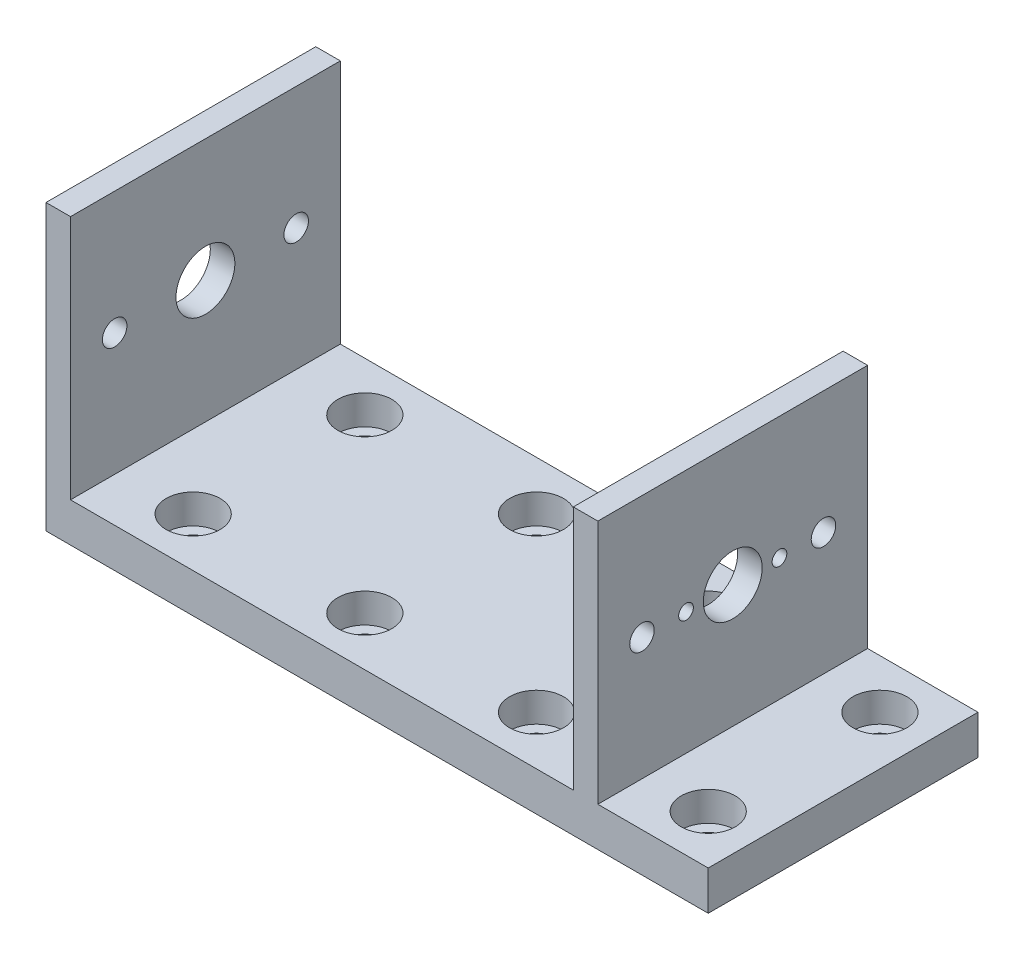
SolidWorks part; units mm, degrees
ref_plane "Front Plane" through (0, 0, 0) normal (0, 0, 1) x (1, 0, 0)
ref_plane "Top Plane" through (0, 0, 0) normal (0, 1, 0) x (1, 0, 0)
ref_plane "Right Plane" through (0, 0, 0) normal (1, 0, 0) x (0, 0, -1)
sketch "Sketch1" plane through (0, 0, 0) normal (0, 1, 0) x (1, 0, 0)
  line L0 (0, 14.013) -> (0, -13.1268) construction
  line L1 (-3.8771, 0) -> (4.5418, 0) construction
  line L2 (-35, 17.5) -> (-35, -17.5) construction
  line L3 (62.5, 27.5) -> (-62.5, 27.5)
  line L4 (-62.5, 27.5) -> (-62.5, -27.5)
  line L5 (62.5, -27.5) -> (-62.5, -27.5)
  line L6 (62.5, 27.5) -> (62.5, -27.5)
  circle A0 centre (-35, 0) radius 10 construction
  circle A1 centre (-52.5, 17.5) radius 3.25
  circle A2 centre (-52.5, -17.5) radius 3.25
  circle A3 centre (-17.5, -17.5) radius 3.25
  circle A4 centre (-17.5, 17.5) radius 3.25
  circle A5 centre (52.5, -17.5) radius 3.25
  circle A6 centre (17.5, -17.5) radius 3.25
  circle A7 centre (17.5, 17.5) radius 3.25
  circle A8 centre (35, 0) radius 10 construction
  circle A9 centre (52.5, 17.5) radius 3.25
  circle A10 centre (-52.5, 17.5) radius 5.5 construction
  circle A11 centre (-17.5, 17.5) radius 5.5 construction
  circle A12 centre (-17.5, -17.5) radius 5.5 construction
  circle A13 centre (-52.5, -17.5) radius 5.5 construction
  circle A14 centre (17.5, -17.5) radius 5.5 construction
  circle A15 centre (17.5, 17.5) radius 5.5 construction
  circle A16 centre (52.5, 17.5) radius 5.5 construction
  circle A17 centre (52.5, -17.5) radius 5.5 construction
  point P19 (-62.5, 0)
  point P33 (0, -27.5)
  point P34 (0, 27.5)
  dimension "D1" = 20
  dimension "D2" = 6.5
  dimension "D10" = 11
  dimension "D3" = 35
  dimension "D4" = 35
  dimension "D5" = 70
  dimension "D6" = 10
  dimension "D7" = 10
  dimension "D8" = 55
  dimension "D9" = 125
extrude "Boss-Extrude1" add sketch "Sketch1" along normal blind 8
sketch "Sketch5" plane through (0, 8, 0) normal (0, 1, 0) x (1, 0, 0)
  circle A0 centre (-52.5, 17.5) radius 5.5
  circle A1 centre (-17.5, 17.5) radius 5.5
  circle A2 centre (17.5, 17.5) radius 5.5
  circle A3 centre (52.5, 17.5) radius 5.5
  circle A4 centre (52.5, -17.5) radius 5.5
  circle A5 centre (17.5, -17.5) radius 5.5
  circle A6 centre (-17.5, -17.5) radius 5.5
  circle A7 centre (-52.5, -17.5) radius 5.5
  dimension "D1" = 11
extrude "Cut-Extrude1" cut sketch "Sketch5" against normal blind 6
sketch "Sketch3" plane through (-62.5, 0, 0) normal (-1, 0, 0) x (0, 0, 1)
  line L0 (-27.5, 0) -> (-27.5, 8)
  line L1 (-27.5, 8) -> (27.5, 8) construction
  line L2 (-27.5, 8) -> (27.5, 8)
  line L3 (27.5, 8) -> (27.5, 0)
  line L4 (27.5, 0) -> (-27.5, 0)
extrude "Boss-Extrude3" add sketch "Sketch3" along normal blind 10
sketch "Sketch4" plane through (0, 8, 0) normal (0, 1, 0) x (1, 0, 0)
  line L0 (-72.5, 27.5) -> (-72.5, -27.5)
  line L1 (-72.5, -27.5) -> (-67.5, -27.5)
  line L2 (-72.5, -27.5) -> (62.5, -27.5) construction
  line L3 (-67.5, -27.5) -> (-67.5, 27.5)
  line L4 (62.5, 27.5) -> (-72.5, 27.5) construction
  line L5 (-67.5, 27.5) -> (-72.5, 27.5)
  line L6 (37.5, 27.5) -> (37.5, -27.5) construction
  line L11 (62.5, -27.5) -> (62.5, 27.5) construction
  line L12 (40, 27.5) -> (35, 27.5)
  line L13 (35, 27.5) -> (35, -27.5)
  line L14 (35, -27.5) -> (40, -27.5)
  line L15 (40, 27.5) -> (40, -27.5)
  dimension "D1" = 5
  dimension "D2" = 25
  dimension "D3" = 5
extrude "Boss-Extrude4" add sketch "Sketch4" along normal blind 50
sketch "Sketch6" plane through (-72.5, 0, 0) normal (-1, 0, 0) x (0, 0, 1)
  line L0 (-27.5, 8) -> (27.5, 8) construction
  line L1 (-27.5, 58) -> (-27.5, 0) construction
  line L2 (27.5, 0) -> (27.5, 58) construction
  line L3 (-27.5, 0) -> (27.5, 0) construction
  line L4 (0, 58) -> (0, 8) construction
  line L5 (-27.5, 58) -> (27.5, 58) construction
  line L6 (0, 33) -> (-27.5, 33) construction
  line L7 (0, 33) -> (27.5, 33) construction
  circle A0 centre (0, 33) radius 6
  circle A1 centre (-18.5, 33) radius 2.5
  circle A2 centre (18.5, 33) radius 2.5
  dimension "D2" = 12
  dimension "D3" = 5
  dimension "D1" = 8
  dimension "D4" = 37
extrude "Cut-Extrude2" cut sketch "Sketch6" against normal through all both and the other way through all
sketch "Sketch8" plane through (40, 0, 0) normal (1, 0, 0) x (0, 0, -1)
  line L0 (-9.525, 33) -> (9.525, 33) construction
  circle A0 centre (0, 33) radius 9.525 construction
  circle A1 centre (9.525, 33) radius 1.5
  circle A2 centre (-9.525, 33) radius 1.5
  dimension "D1" = 19.05
  dimension "D2" = 3
extrude "Cut-Extrude3" cut sketch "Sketch8" against normal blind 10
